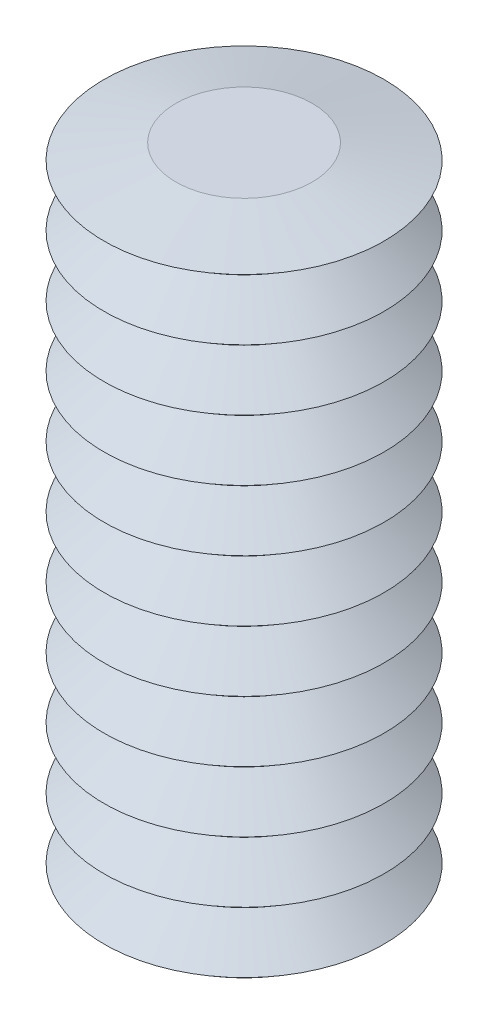
SolidWorks part; units mm, degrees
material "AISI 304"
ref_plane "Alzado" through (0, 0, 0) normal (0, 0, 1) x (1, 0, 0)
ref_plane "Planta" through (0, 0, 0) normal (0, 1, 0) x (1, 0, 0)
ref_plane "Vista lateral" through (0, 0, 0) normal (1, 0, 0) x (0, 0, -1)
sketch "Sketch1" plane through (0, 0, 0) normal (0, 0, 1) x (1, 0, 0)
  line L0 (0, 0) -> (2.24, 0)
  line L1 (2.24, 0) -> (4.6, -0.5)
  line L2 (4.6, -0.5) -> (3.2, -1.5)
  line L3 (3.2, -1.5) -> (4.6, -2.5)
  line L4 (4.6, -2.5) -> (3.2, -3.5)
  line L5 (3.2, -3.5) -> (4.6, -4.5)
  line L6 (4.6, -4.5) -> (3.2, -5.5)
  line L7 (3.2, -5.5) -> (4.6, -6.5)
  line L8 (4.6, -6.5) -> (3.2, -7.5)
  line L9 (3.2, -7.5) -> (4.6, -8.5)
  line L10 (4.6, -8.5) -> (3.2, -9.5)
  line L11 (3.2, -9.5) -> (4.6, -10.5)
  line L12 (4.6, -10.5) -> (3.2, -11.5)
  line L13 (3.2, -11.5) -> (4.6, -12.5)
  line L14 (4.6, -12.5) -> (3.2, -13.5)
  line L15 (3.2, -13.5) -> (4.6, -14.5)
  line L16 (4.6, -14.5) -> (3.2, -15.5)
  line L17 (3.2, -15.5) -> (4.6, -16.5)
  line L18 (4.6, -16.5) -> (3.2, -17.5)
  line L19 (3.2, -17.5) -> (4.6, -18.5)
  line L20 (4.6, -18.5) -> (3.2, -19.5)
  line L21 (3.2, -19.5) -> (4.6, -20.5)
  line L22 (4.6, -20.5) -> (3.2, -21.5)
  line L23 (3.2, -21.5) -> (2.24, -22)
  line L24 (2.24, -22) -> (0, -22)
  line L25 (0, -22) -> (0, 0)
  line L26 (0, -26) -> (0, 4) construction
revolve "Elemento_elastico_en_serie" add sketch "Sketch1" angle 360 about L26
